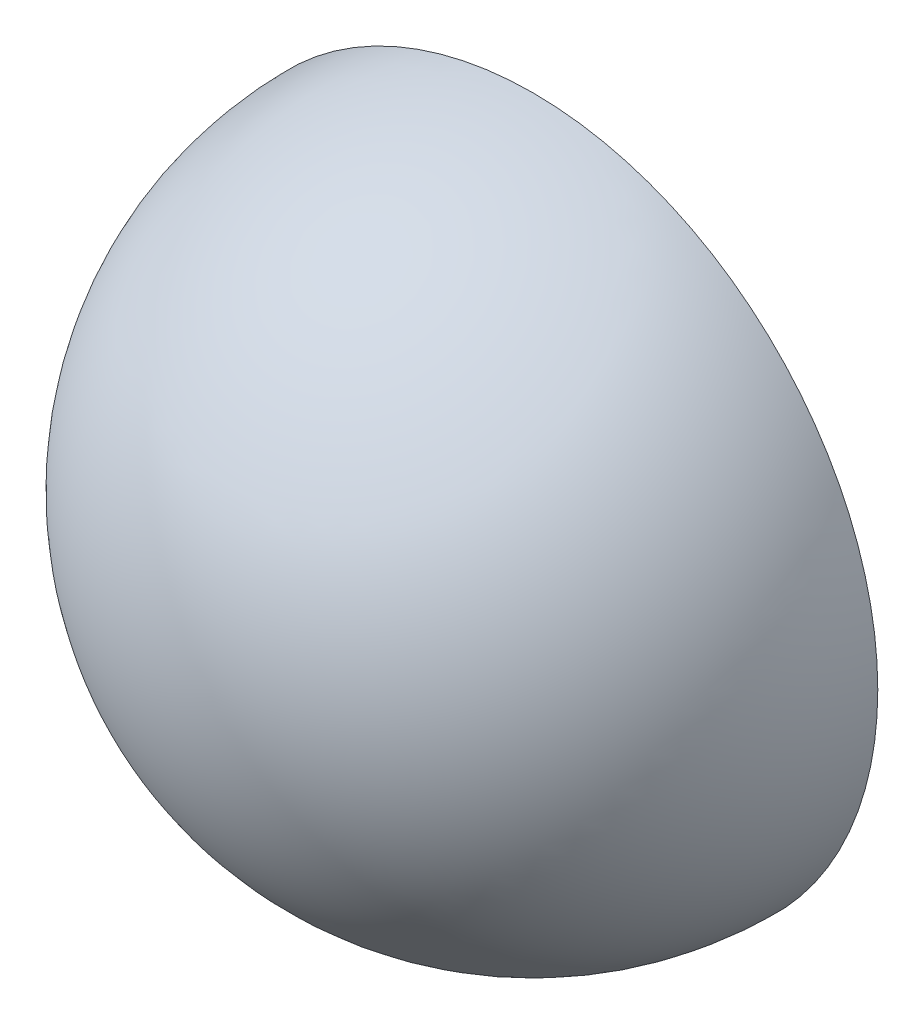
SolidWorks part; units mm, degrees
ref_plane "Front" through (0, 0, 0) normal (0, 0, 1) x (1, 0, 0)
ref_plane "Top" through (0, 0, 0) normal (0, 1, 0) x (1, 0, 0)
ref_plane "Right" through (0, 0, 0) normal (1, 0, 0) x (0, 0, -1)
sketch "Sketch1" plane through (0, 0, 0) normal (1, 0, 0) x (0, 0, -1)
  line L0 (0, 0) -> (-12.9179, 0) construction
  line L1 (0, 0) -> (0, 2.5)
  line L2 (-2.5, 0) -> (0, 0)
  arc A0 (0, 2.5) -> (-2.5, 0) centre (0, 0) ccw
  dimension "D1" = 2.5
revolve "Revolve1" add sketch "Sketch1" angle 360 about L0
sketch "Sketch2" plane through (0, 0, 0) normal (0, 0, -1) x (-1, 0, 0)
  circle A0 centre (0, 0) radius 1.255
  dimension "D1" = 2.51
extrude "Cut-Extrude1" cut sketch "Sketch2" against normal blind 1.5
cosmetic thread "Cosmetic Thread1" parameters "D2"=3
